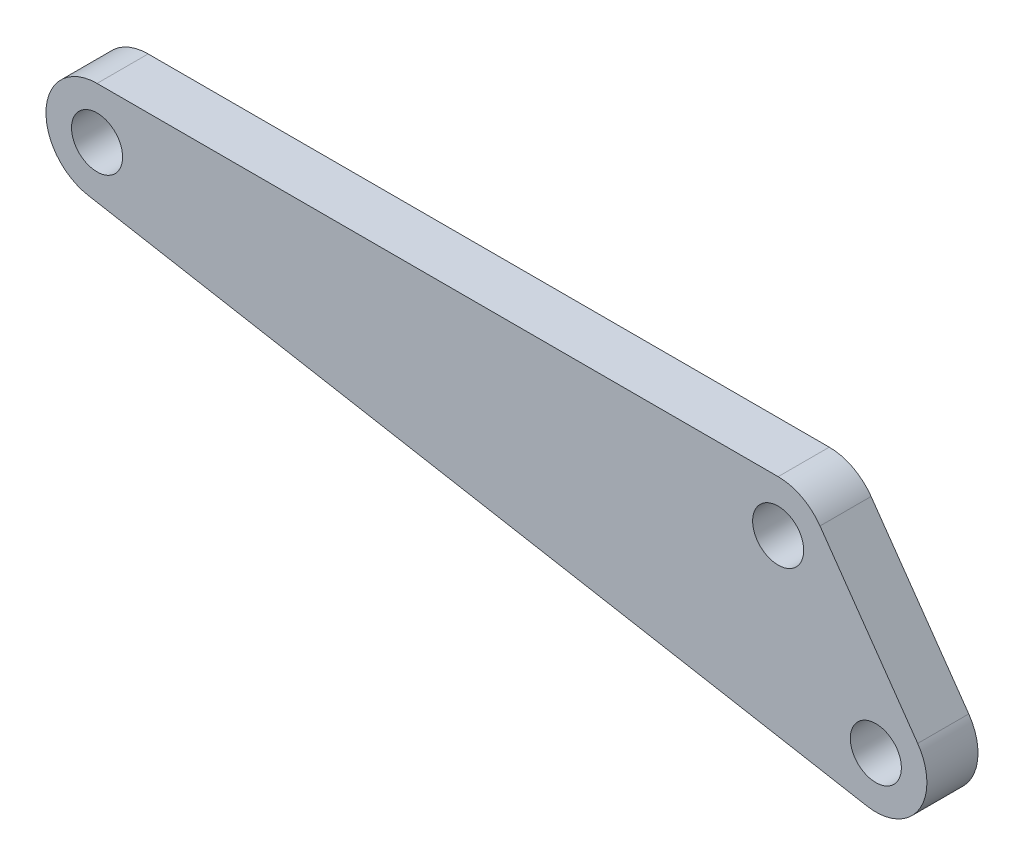
SolidWorks part; units mm, degrees
ref_plane "Front Plane" through (0, 0, 0) normal (0, 0, 1) x (1, 0, 0)
ref_plane "Top Plane" through (0, 0, 0) normal (0, 1, 0) x (1, 0, 0)
ref_plane "Right Plane" through (0, 0, 0) normal (1, 0, 0) x (0, 0, -1)
sketch "Sketch1" plane through (0, 0, 0) normal (0, 0, 1) x (1, 0, 0)
  line L0 (0, 0) -> (-40, 0)
  line L1 (0, 0) -> (5.7358, -8.1915)
  dimension "D1" = 40
  dimension "D2" = 10
  dimension "D3" = 125
sketch "Sketch2" plane through (0, 0, 0) normal (0, 0, 1) x (1, 0, 0)
  line L0 (-40, 3) -> (0, 3)
  line L1 (2.4575, 1.7207) -> (8.1932, -6.4708)
  line L2 (5.2069, -11.1445) -> (-40.5289, -2.953)
  circle A0 centre (-40, 0) radius 1.5
  arc A1 (-40, 3) -> (-40.5289, -2.953) centre (-40, 0) ccw
  circle A2 centre (0, 0) radius 1.5
  arc A3 (2.4575, 1.7207) -> (0, 3) centre (0, 0) ccw
  circle A4 centre (5.7358, -8.1915) radius 1.5
  arc A5 (5.2069, -11.1445) -> (8.1932, -6.4708) centre (5.7358, -8.1915) ccw
  dimension "D1" = 3
  dimension "D2" = 6
  dimension "D3" = 3
  dimension "D4" = 6
  dimension "D5" = 3
  dimension "D6" = 6
extrude "Boss-Extrude1" add sketch "Sketch2" along normal blind 3
